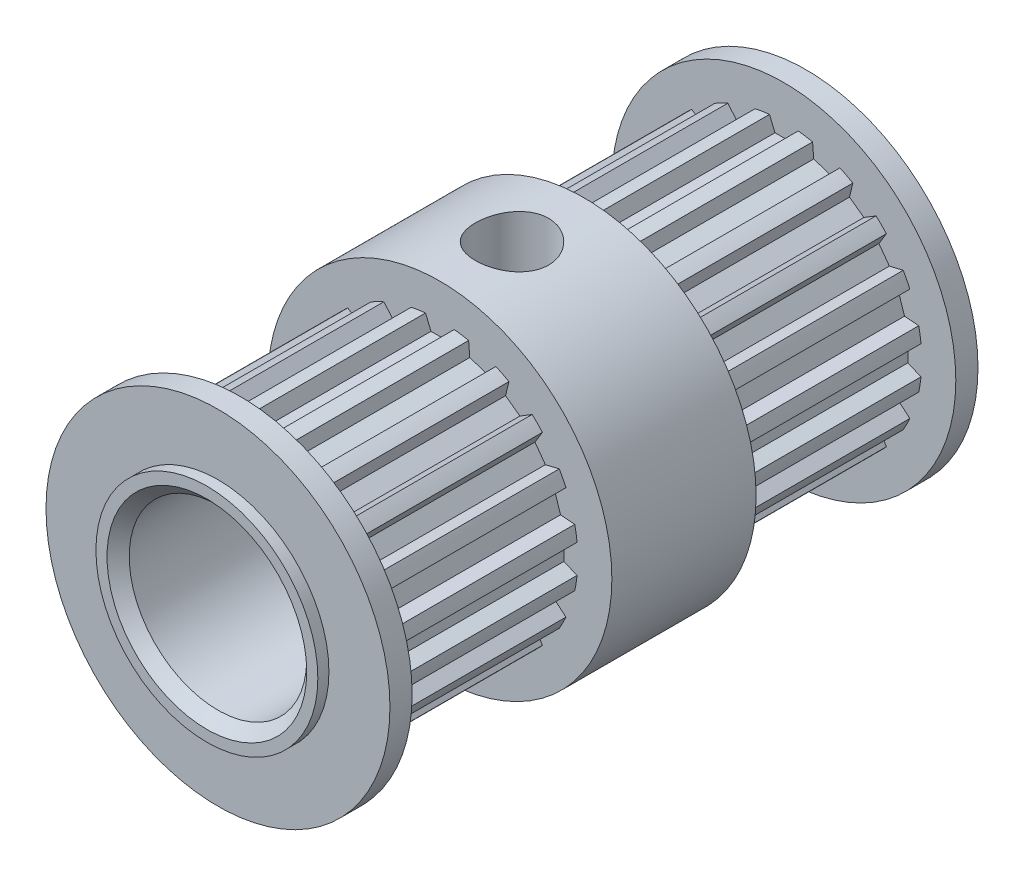
SolidWorks part; units mm, degrees
ref_plane "Alzado" through (0, 0, 0) normal (0, 0, 1) x (1, 0, 0)
ref_plane "Planta" through (0, 0, 0) normal (0, 1, 0) x (1, 0, 0)
ref_plane "Vista lateral" through (0, 0, 0) normal (1, 0, 0) x (0, 0, -1)
ref_plane "Plano1" through (0, 0, 6.5) normal (0, 0, -1) x (-1, 0, 0)
sketch "Croquis1" plane through (0, 0, 6.5) normal (0, 0, -1) x (-1, 0, 0)
  line L0 (-0.6461, -6.1813) -> (-0.4, -5.5872)
  line L1 (-0.4, -5.5872) -> (0.4, -5.5872)
  line L2 (0.4, -5.5872) -> (0.6461, -6.1813)
  line L3 (1.2957, -6.0784) -> (1.3461, -5.4374)
  line L4 (1.3461, -5.4374) -> (2.107, -5.1902)
  line L5 (2.107, -5.1902) -> (2.5246, -5.6791)
  line L6 (3.1106, -5.3806) -> (2.9605, -4.7553)
  line L7 (2.9605, -4.7553) -> (3.6077, -4.2851)
  line L8 (3.6077, -4.2851) -> (4.156, -4.621)
  line L9 (4.621, -4.156) -> (4.2851, -3.6077)
  line L10 (4.2851, -3.6077) -> (4.7553, -2.9605)
  line L11 (4.7553, -2.9605) -> (5.3806, -3.1106)
  line L12 (5.6791, -2.5246) -> (5.1902, -2.107)
  line L13 (5.1902, -2.107) -> (5.4374, -1.3461)
  line L14 (5.4374, -1.3461) -> (6.0784, -1.2957)
  line L15 (6.1813, -0.6461) -> (5.5872, -0.4)
  line L16 (5.5872, -0.4) -> (5.5872, 0.4)
  line L17 (5.5872, 0.4) -> (6.1813, 0.6461)
  line L18 (6.0784, 1.2957) -> (5.4374, 1.3461)
  line L19 (5.4374, 1.3461) -> (5.1902, 2.107)
  line L20 (5.1902, 2.107) -> (5.6791, 2.5246)
  line L21 (5.3806, 3.1106) -> (4.7553, 2.9605)
  line L22 (4.7553, 2.9605) -> (4.2851, 3.6077)
  line L23 (4.2851, 3.6077) -> (4.621, 4.156)
  line L24 (4.156, 4.621) -> (3.6077, 4.2851)
  line L25 (3.6077, 4.2851) -> (2.9605, 4.7553)
  line L26 (2.9605, 4.7553) -> (3.1106, 5.3806)
  line L27 (2.5246, 5.6791) -> (2.107, 5.1902)
  line L28 (2.107, 5.1902) -> (1.3461, 5.4374)
  line L29 (1.3461, 5.4374) -> (1.2957, 6.0784)
  line L30 (0.6461, 6.1813) -> (0.4, 5.5872)
  line L31 (0.4, 5.5872) -> (-0.4, 5.5872)
  line L32 (-0.4, 5.5872) -> (-0.6461, 6.1813)
  line L33 (-1.2957, 6.0784) -> (-1.3461, 5.4374)
  line L34 (-1.3461, 5.4374) -> (-2.107, 5.1902)
  line L35 (-2.107, 5.1902) -> (-2.5246, 5.6791)
  line L36 (-3.1106, 5.3806) -> (-2.9605, 4.7553)
  line L37 (-2.9605, 4.7553) -> (-3.6077, 4.2851)
  line L38 (-3.6077, 4.2851) -> (-4.156, 4.621)
  line L39 (-4.621, 4.156) -> (-4.2851, 3.6077)
  line L40 (-4.2851, 3.6077) -> (-4.7553, 2.9605)
  line L41 (-4.7553, 2.9605) -> (-5.3806, 3.1106)
  line L42 (-5.6791, 2.5246) -> (-5.1902, 2.107)
  line L43 (-5.1902, 2.107) -> (-5.4374, 1.3461)
  line L44 (-5.4374, 1.3461) -> (-6.0784, 1.2957)
  line L45 (-6.1813, 0.6461) -> (-5.5872, 0.4)
  line L46 (-5.5872, 0.4) -> (-5.5872, -0.4)
  line L47 (-5.5872, -0.4) -> (-6.1813, -0.6461)
  line L48 (-6.0784, -1.2957) -> (-5.4374, -1.3461)
  line L49 (-5.4374, -1.3461) -> (-5.1902, -2.107)
  line L50 (-5.1902, -2.107) -> (-5.6791, -2.5246)
  line L51 (-5.3806, -3.1106) -> (-4.7553, -2.9605)
  line L52 (-4.7553, -2.9605) -> (-4.2851, -3.6077)
  line L53 (-4.2851, -3.6077) -> (-4.621, -4.156)
  line L54 (-4.156, -4.621) -> (-3.6077, -4.2851)
  line L55 (-3.6077, -4.2851) -> (-2.9605, -4.7553)
  line L56 (-2.9605, -4.7553) -> (-3.1106, -5.3806)
  line L57 (-2.5246, -5.6791) -> (-2.107, -5.1902)
  line L58 (-2.107, -5.1902) -> (-1.3461, -5.4374)
  line L59 (-1.3461, -5.4374) -> (-1.2957, -6.0784)
  arc A0 (-1.2957, -6.0784) -> (-0.6461, -6.1813) centre (0, 0) ccw
  arc A1 (0.6461, -6.1813) -> (1.2957, -6.0784) centre (0, 0) ccw
  arc A2 (2.5246, -5.6791) -> (3.1106, -5.3806) centre (0, 0) ccw
  arc A3 (4.156, -4.621) -> (4.621, -4.156) centre (0, 0) ccw
  arc A4 (5.3806, -3.1106) -> (5.6791, -2.5246) centre (0, 0) ccw
  arc A5 (6.0784, -1.2957) -> (6.1813, -0.6461) centre (0, 0) ccw
  arc A6 (6.1813, 0.6461) -> (6.0784, 1.2957) centre (0, 0) ccw
  arc A7 (5.6791, 2.5246) -> (5.3806, 3.1106) centre (0, 0) ccw
  arc A8 (4.621, 4.156) -> (4.156, 4.621) centre (0, 0) ccw
  arc A9 (3.1106, 5.3806) -> (2.5246, 5.6791) centre (0, 0) ccw
  arc A10 (1.2957, 6.0784) -> (0.6461, 6.1813) centre (0, 0) ccw
  arc A11 (-0.6461, 6.1813) -> (-1.2957, 6.0784) centre (0, 0) ccw
  arc A12 (-2.5246, 5.6791) -> (-3.1106, 5.3806) centre (0, 0) ccw
  arc A13 (-4.156, 4.621) -> (-4.621, 4.156) centre (0, 0) ccw
  arc A14 (-5.3806, 3.1106) -> (-5.6791, 2.5246) centre (0, 0) ccw
  arc A15 (-6.0784, 1.2957) -> (-6.1813, 0.6461) centre (0, 0) ccw
  arc A16 (-6.1813, -0.6461) -> (-6.0784, -1.2957) centre (0, 0) ccw
  arc A17 (-5.6791, -2.5246) -> (-5.3806, -3.1106) centre (0, 0) ccw
  arc A18 (-4.621, -4.156) -> (-4.156, -4.621) centre (0, 0) ccw
  arc A19 (-3.1106, -5.3806) -> (-2.5246, -5.6791) centre (0, 0) ccw
extrude "Saliente-Extruir1" add sketch "Croquis1" against normal blind 9
ref_plane "Plano2" through (0, 0, 15.5) normal (0, 0, -1) x (-1, 0, 0)
sketch "Croquis2" plane through (0, 0, 15.5) normal (0, 0, -1) x (-1, 0, 0)
  circle A0 centre (0, 0) radius 7.75
extrude "Saliente-Extruir2" add sketch "Croquis2" against normal blind 1
ref_plane "Plano3" through (0, 0, 6.5) normal (0, 0, 1) x (1, 0, 0)
sketch "Croquis3" plane through (0, 0, 6.5) normal (0, 0, 1) x (1, 0, 0)
  circle A0 centre (0, 0) radius 7.75
extrude "Saliente-Extruir3" add sketch "Croquis3" against normal blind 6.5
sketch "Croquis4" plane through (0, 0, 0) normal (0, 0, -1) x (-1, 0, 0)
  line L0 (-5.1902, 2.107) -> (-5.6791, 2.5246)
  line L1 (-5.3806, 3.1106) -> (-4.7553, 2.9605)
  line L2 (-4.7553, 2.9605) -> (-4.2851, 3.6077)
  line L3 (-4.2851, 3.6077) -> (-4.621, 4.156)
  line L4 (-4.156, 4.621) -> (-3.6077, 4.2851)
  line L5 (-3.6077, 4.2851) -> (-2.9605, 4.7553)
  line L6 (-2.9605, 4.7553) -> (-3.1106, 5.3806)
  line L7 (-2.5246, 5.6791) -> (-2.107, 5.1902)
  line L8 (-2.107, 5.1902) -> (-1.3461, 5.4374)
  line L9 (-1.3461, 5.4374) -> (-1.2957, 6.0784)
  line L10 (-0.6461, 6.1813) -> (-0.4, 5.5872)
  line L11 (-0.4, 5.5872) -> (0.4, 5.5872)
  line L12 (0.4, 5.5872) -> (0.6461, 6.1813)
  line L13 (1.2957, 6.0784) -> (1.3461, 5.4374)
  line L14 (1.3461, 5.4374) -> (2.107, 5.1902)
  line L15 (2.107, 5.1902) -> (2.5246, 5.6791)
  line L16 (3.1106, 5.3806) -> (2.9605, 4.7553)
  line L17 (2.9605, 4.7553) -> (3.6077, 4.2851)
  line L18 (3.6077, 4.2851) -> (4.156, 4.621)
  line L19 (4.621, 4.156) -> (4.2851, 3.6077)
  line L20 (4.2851, 3.6077) -> (4.7553, 2.9605)
  line L21 (4.7553, 2.9605) -> (5.3806, 3.1106)
  line L22 (5.6791, 2.5246) -> (5.1902, 2.107)
  line L23 (5.1902, 2.107) -> (5.4374, 1.3461)
  line L24 (5.4374, 1.3461) -> (6.0784, 1.2957)
  line L25 (6.1813, 0.6461) -> (5.5872, 0.4)
  line L26 (5.5872, 0.4) -> (5.5872, -0.4)
  line L27 (5.5872, -0.4) -> (6.1813, -0.6461)
  line L28 (6.0784, -1.2957) -> (5.4374, -1.3461)
  line L29 (5.4374, -1.3461) -> (5.1902, -2.107)
  line L30 (5.1902, -2.107) -> (5.6791, -2.5246)
  line L31 (5.3806, -3.1106) -> (4.7553, -2.9605)
  line L32 (4.7553, -2.9605) -> (4.2851, -3.6077)
  line L33 (4.2851, -3.6077) -> (4.621, -4.156)
  line L34 (4.156, -4.621) -> (3.6077, -4.2851)
  line L35 (3.6077, -4.2851) -> (2.9605, -4.7553)
  line L36 (2.9605, -4.7553) -> (3.1106, -5.3806)
  line L37 (2.5246, -5.6791) -> (2.107, -5.1902)
  line L38 (2.107, -5.1902) -> (1.3461, -5.4374)
  line L39 (1.3461, -5.4374) -> (1.2957, -6.0784)
  line L40 (0.6461, -6.1813) -> (0.4, -5.5872)
  line L41 (0.4, -5.5872) -> (-0.4, -5.5872)
  line L42 (-0.4, -5.5872) -> (-0.6461, -6.1813)
  line L43 (-1.2957, -6.0784) -> (-1.3461, -5.4374)
  line L44 (-1.3461, -5.4374) -> (-2.107, -5.1902)
  line L45 (-2.107, -5.1902) -> (-2.5246, -5.6791)
  line L46 (-3.1106, -5.3806) -> (-2.9605, -4.7553)
  line L47 (-2.9605, -4.7553) -> (-3.6077, -4.2851)
  line L48 (-3.6077, -4.2851) -> (-4.156, -4.621)
  line L49 (-4.621, -4.156) -> (-4.2851, -3.6077)
  line L50 (-4.2851, -3.6077) -> (-4.7553, -2.9605)
  line L51 (-4.7553, -2.9605) -> (-5.3806, -3.1106)
  line L52 (-5.6791, -2.5246) -> (-5.1902, -2.107)
  line L53 (-5.1902, -2.107) -> (-5.4374, -1.3461)
  line L54 (-5.4374, -1.3461) -> (-6.0784, -1.2957)
  line L55 (-6.1813, -0.6461) -> (-5.5872, -0.4)
  line L56 (-5.5872, -0.4) -> (-5.5872, 0.4)
  line L57 (-5.5872, 0.4) -> (-6.1813, 0.6461)
  line L58 (-6.0784, 1.2957) -> (-5.4374, 1.3461)
  line L59 (-5.4374, 1.3461) -> (-5.1902, 2.107)
  arc A0 (-5.6791, 2.5246) -> (-5.3806, 3.1106) centre (0, 0) cw
  arc A1 (-4.621, 4.156) -> (-4.156, 4.621) centre (0, 0) cw
  arc A2 (-3.1106, 5.3806) -> (-2.5246, 5.6791) centre (0, 0) cw
  arc A3 (-1.2957, 6.0784) -> (-0.6461, 6.1813) centre (0, 0) cw
  arc A4 (0.6461, 6.1813) -> (1.2957, 6.0784) centre (0, 0) cw
  arc A5 (2.5246, 5.6791) -> (3.1106, 5.3806) centre (0, 0) cw
  arc A6 (4.156, 4.621) -> (4.621, 4.156) centre (0, 0) cw
  arc A7 (5.3806, 3.1106) -> (5.6791, 2.5246) centre (0, 0) cw
  arc A8 (6.0784, 1.2957) -> (6.1813, 0.6461) centre (0, 0) cw
  arc A9 (6.1813, -0.6461) -> (6.0784, -1.2957) centre (0, 0) cw
  arc A10 (5.6791, -2.5246) -> (5.3806, -3.1106) centre (0, 0) cw
  arc A11 (4.621, -4.156) -> (4.156, -4.621) centre (0, 0) cw
  arc A12 (3.1106, -5.3806) -> (2.5246, -5.6791) centre (0, 0) cw
  arc A13 (1.2957, -6.0784) -> (0.6461, -6.1813) centre (0, 0) cw
  arc A14 (-0.6461, -6.1813) -> (-1.2957, -6.0784) centre (0, 0) cw
  arc A15 (-2.5246, -5.6791) -> (-3.1106, -5.3806) centre (0, 0) cw
  arc A16 (-4.156, -4.621) -> (-4.621, -4.156) centre (0, 0) cw
  arc A17 (-5.3806, -3.1106) -> (-5.6791, -2.5246) centre (0, 0) cw
  arc A18 (-6.0784, -1.2957) -> (-6.1813, -0.6461) centre (0, 0) cw
  arc A19 (-6.1813, 0.6461) -> (-6.0784, 1.2957) centre (0, 0) cw
extrude "Saliente-Extruir4" add sketch "Croquis4" along normal blind 9
ref_plane "Plano4" through (0, 0, -9) normal (0, 0, 1) x (1, 0, 0)
sketch "Croquis5" plane through (0, 0, -9) normal (0, 0, 1) x (1, 0, 0)
  circle A0 centre (0, 0) radius 7.75
extrude "Saliente-Extruir5" add sketch "Croquis5" against normal blind 1
sketch "Croquis6" plane through (0, 0, 16.5) normal (0, 0, 1) x (1, 0, 0)
  circle A0 centre (0, 0) radius 5
extrude "Saliente-Extruir6" add sketch "Croquis6" along normal blind 0.5
sketch "Croquis7" plane through (0, 0, -10) normal (0, 0, -1) x (-1, 0, 0)
  circle A0 centre (0, 0) radius 5
extrude "Saliente-Extruir7" add sketch "Croquis7" along normal blind 0.5
hole_wizard "Diámetro de taladro Ø8.0 (8)1" positions "Croquis9" profile "Croquis8" hole size "Ø8.0" standard "Ansi Metric"
sketch "Croquis9" plane through (0, 0, 17) normal (0, 0, 1) x (1, 0, 0)
  point P0 (0, 0)
sketch "Croquis8" plane through (0, 0, 17) normal (1, 0, 0) x (0, -1, 0)
  line L0 (0, 0) -> (0, 27.5)
  line L1 (0, 27.5) -> (4, 27.5)
  line L2 (4, 27.5) -> (4, 0)
  line L5 (4, 0) -> (0, 0)
  line L11 (0, -6.35) -> (0, 107.95) construction
  dimension "Diámetro de taladro hasta el siguiente" = 8
  dimension "Profundidad de taladro hasta el siguiente" = 27.5
hole_wizard "Taladro de margen para M3.51" positions "Croquis3D1" profile "Croquis10" hole size "M3.5" standard "Ansi Metric"
sketch3d "Croquis3D1"
  point P0 (0, 7.75, 3.25)
sketch "Croquis10" plane through (0, 7.75, 3.25) normal (1, 0, 0) x (0, 0, 1)
  line L0 (0, 0) -> (0, 3.75)
  line L1 (0, 3.75) -> (1.65, 3.75)
  line L2 (1.65, 3.75) -> (1.65, 0)
  line L5 (1.65, 0) -> (0, 0)
  line L11 (0, -6.35) -> (0, 107.95) construction
  dimension "Diámetro de taladro hasta el siguiente" = 3.3
  dimension "Profundidad de taladro hasta el siguiente" = 3.75
chamfer "Chaflán1" distance 0.5 angle 45 2 edges at (4, 0, -10.5) (4, 0, 17)
